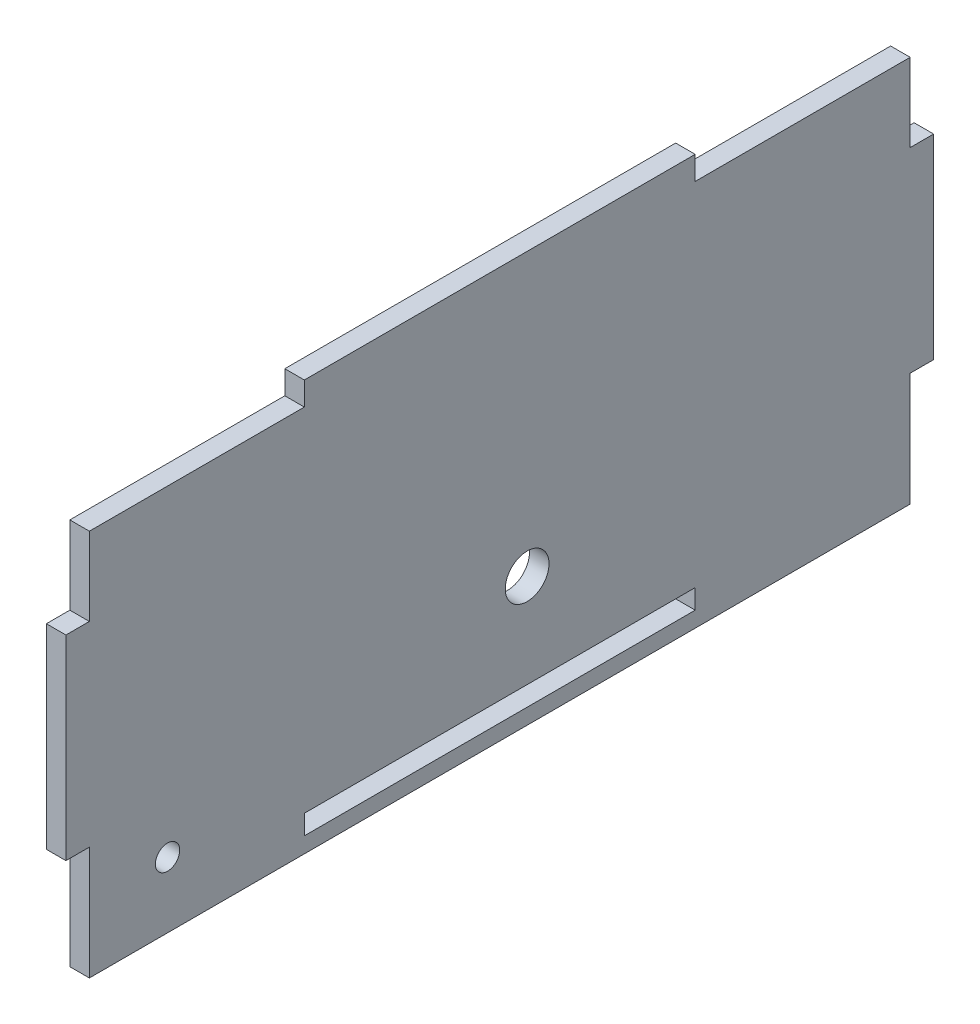
SolidWorks part; units mm, degrees
ref_plane "Front Plane" through (0, 0, 0) normal (0, 0, 1) x (1, 0, 0)
ref_plane "Top Plane" through (0, 0, 0) normal (0, 1, 0) x (1, 0, 0)
ref_plane "Right Plane" through (0, 0, 0) normal (1, 0, 0) x (0, 0, -1)
sketch "Sketch1" plane through (0, 0, 0) normal (1, 0, 0) x (0, 0, -1)
  line L0 (-66.675, -28.575) -> (-31.75, -28.575) construction
  line L1 (-66.675, 28.575) -> (-31.75, 28.575)
  line L2 (-66.675, 28.575) -> (-66.675, 15.875)
  line L3 (-66.675, -34.29) -> (66.675, -34.29)
  line L4 (66.675, 28.575) -> (66.675, 15.875)
  line L5 (0, 28.575) -> (0, 0) construction
  line L6 (31.75, 28.575) -> (31.75, 32.385)
  line L7 (31.75, 32.385) -> (-31.75, 32.385)
  line L8 (-31.75, 28.575) -> (-31.75, 32.385)
  line L9 (-31.75, -28.575) -> (31.75, -28.575)
  line L10 (-31.75, -28.575) -> (-31.75, -31.75)
  line L11 (-31.75, -31.75) -> (31.75, -31.75)
  line L12 (31.75, -28.575) -> (31.75, -31.75)
  line L13 (31.75, -28.575) -> (66.675, -28.575) construction
  line L14 (31.75, 28.575) -> (66.675, 28.575)
  line L15 (0, 0) -> (0, -28.575) construction
  line L16 (0, -28.575) -> (0, -31.75) construction
  line L17 (70.485, 0) -> (-70.485, 0) construction
  line L18 (-66.675, -15.875) -> (-66.675, -34.29)
  line L19 (-66.675, 15.875) -> (-70.485, 15.875)
  line L20 (66.675, -15.875) -> (66.675, -34.29)
  line L21 (-66.675, -15.875) -> (-70.485, -15.875)
  line L22 (-70.485, 15.875) -> (-70.485, -15.875)
  line L23 (66.675, 15.875) -> (70.485, 15.875)
  line L24 (-66.675, 15.875) -> (-66.675, -15.875) construction
  line L25 (66.675, -15.875) -> (70.485, -15.875)
  line L26 (70.485, 15.875) -> (70.485, -15.875)
  line L27 (-53.975, -23.6347) -> (-66.675, -23.6347) construction
  line L29 (-31.75, 28.575) -> (31.75, 28.575) construction
  circle A0 centre (-53.975, -23.6347) radius 4.9403 construction
  circle A1 centre (4.445, -13.335) radius 3.556
  circle A3 centre (-53.975, -23.6347) radius 1.9812
  dimension "D13" = 9.8806
  dimension "D18" = 3.9624
  dimension "D15" = 7.112
  dimension "D1" = 133.35
  dimension "D2" = 57.15
  dimension "D3" = 3.81
  dimension "D4" = 63.5
  dimension "D5" = 3.175
  dimension "D6" = 63.5
  dimension "D7" = 2.54
  dimension "D8" = 3.81
  dimension "D9" = 3.81
  dimension "D10" = 31.75
  dimension "D11" = 31.75
  dimension "D12" = 12.7
  dimension "D14" = 71.12
  dimension "D16" = 15.24
extrude "Boss-Extrude1" add sketch "Sketch1" along normal blind 3.175
